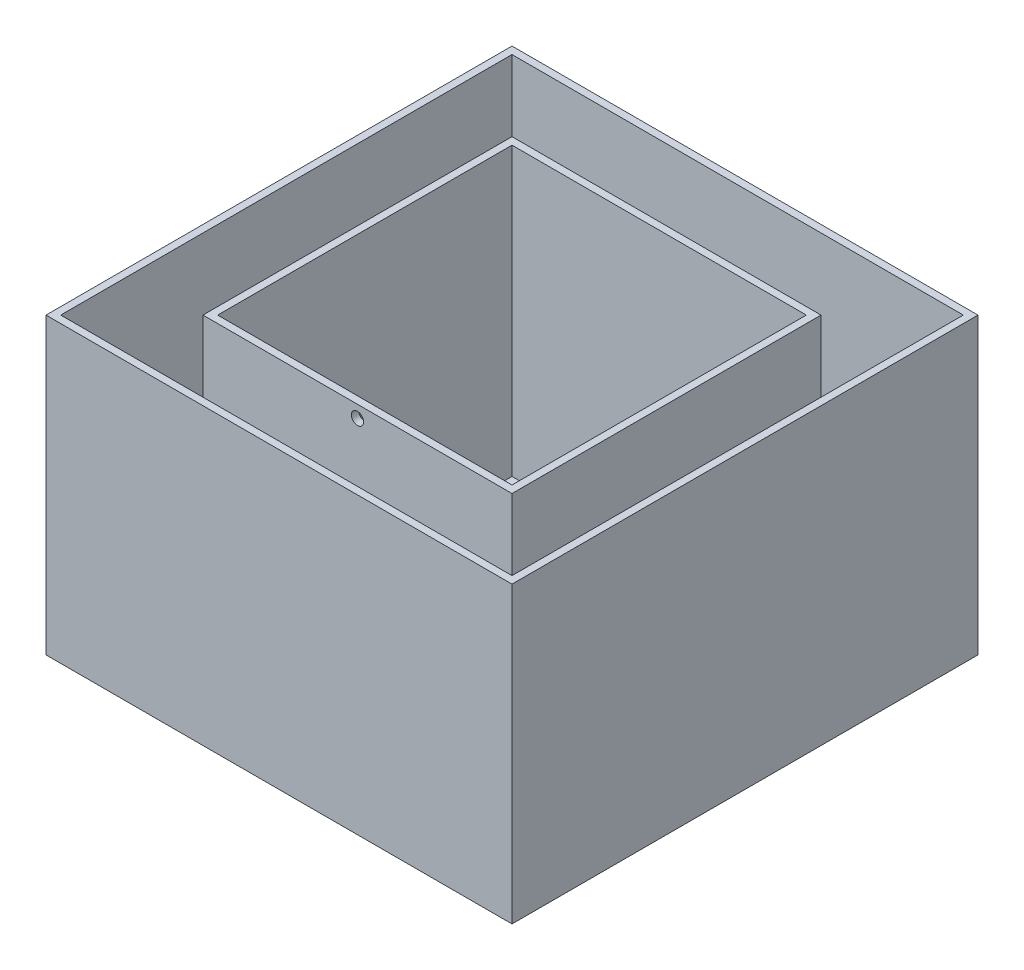
SolidWorks part; units mm, degrees
ref_plane "Front Plane" through (0, 0, 0) normal (0, 0, 1) x (1, 0, 0)
ref_plane "Top Plane" through (0, 0, 0) normal (0, 1, 0) x (1, 0, 0)
ref_plane "Right Plane" through (0, 0, 0) normal (1, 0, 0) x (0, 0, -1)
sketch "Sketch1" plane through (0, 0, 0) normal (0, 1, 0) x (1, 0, 0)
  line L1 (-95, -95) -> (95, -95)
  line L2 (-95, -95) -> (-95, 95)
  line L3 (-95, 95) -> (95, 95)
  line L4 (95, -95) -> (95, 95)
  line L5 (-95, -95) -> (95, 95) construction
  line L6 (-95, 95) -> (95, -95) construction
  point P0 (0, 0)
  dimension "D1" = 190
extrude "Boss-Extrude1" add sketch "Sketch1" along normal blind 120 contours L3 L4 L1 L2
sketch "Sketch2" plane through (0, 120, 0) normal (0, 1, 0) x (1, 0, 0)
  line L1 (-60, -60) -> (60, -60)
  line L2 (-60, -60) -> (-60, 60)
  line L3 (-60, 60) -> (60, 60)
  line L4 (60, -60) -> (60, 60)
  line L5 (-60, -60) -> (60, 60) construction
  line L6 (-60, 60) -> (60, -60) construction
  point P0 (0, 0)
  dimension "D1" = 120
extrude "Cut-Extrude1" cut sketch "Sketch2" against normal blind 117
sketch "Sketch3" plane through (0, 120, 0) normal (0, 1, 0) x (1, 0, 0)
  line L5 (60, -60) -> (60, 60) construction
  line L10 (-63, -63) -> (63, -63)
  line L12 (-63, -63) -> (-63, 63)
  line L13 (-63, 63) -> (63, 63)
  line L17 (63, -63) -> (63, 63)
  line L18 (-63, -63) -> (63, 63) construction
  line L19 (-63, 63) -> (63, -63) construction
  line L20 (-92, 92) -> (92, 92)
  line L21 (92, -92) -> (92, 92)
  line L22 (-92, -92) -> (92, -92)
  line L23 (-92, -92) -> (-92, 92)
  line L25 (-95, -95) -> (-95, 95) construction
  point P0 (0, 0)
  dimension "D1" = 3
  dimension "D2" = 3
extrude "Cut-Extrude2" cut sketch "Sketch3" against normal blind 115
sketch "Sketch4" plane through (0, 5, 0) normal (0, 1, 0) x (1, 0, 0)
  line L3 (-89, -89) -> (-89, 89)
  line L7 (-63, -63) -> (-63, 63)
  line L8 (-92, 92) -> (-92, -92) construction
  line L11 (-89, -89) -> (-63, -63)
  line L16 (-63, 63) -> (-92, 92) construction
  line L17 (0, 95) -> (0, -92) construction
  line L18 (-95, 95) -> (95, 95) construction
  line L19 (-92, -92) -> (92, -92) construction
  line L20 (-95, 0) -> (95, 0) construction
  line L21 (-95, -95) -> (-95, 95) construction
  line L22 (95, -95) -> (95, 95) construction
  line L29 (-89, -89) -> (-89, 79) construction
  line L30 (89, -89) -> (-89, -89) construction
  line L31 (89, 79) -> (89, -89) construction
  line L32 (-89, 79) -> (89, 79) construction
  line L33 (-63, -63) -> (-63, 53) construction
  line L34 (-63, 53) -> (63, 53) construction
  line L35 (63, -63) -> (-63, -63) construction
  line L36 (63, 53) -> (63, -63) construction
  line L37 (-63, 63) -> (-89, 89)
  line L39 (89, -89) -> (63, -63)
  line L40 (89, -89) -> (89, 89)
  line L41 (63, 63) -> (89, 89)
  line L42 (63, -63) -> (63, 63)
  dimension "D1" = 3
extrude "Cut-Extrude3" cut sketch "Sketch4" against normal blind 53
sketch "Sketch5" plane through (0, 0, 63) normal (0, 0, 1) x (1, 0, 0)
  line L0 (0, 120) -> (0, 115) construction
  line L1 (-95, 120) -> (95, 120) construction
  circle A0 centre (0, 115) radius 2.5
  dimension "D2" = 5
  dimension "D1" = 5
extrude "Cut-Extrude4" cut sketch "Sketch5" against normal blind 17
